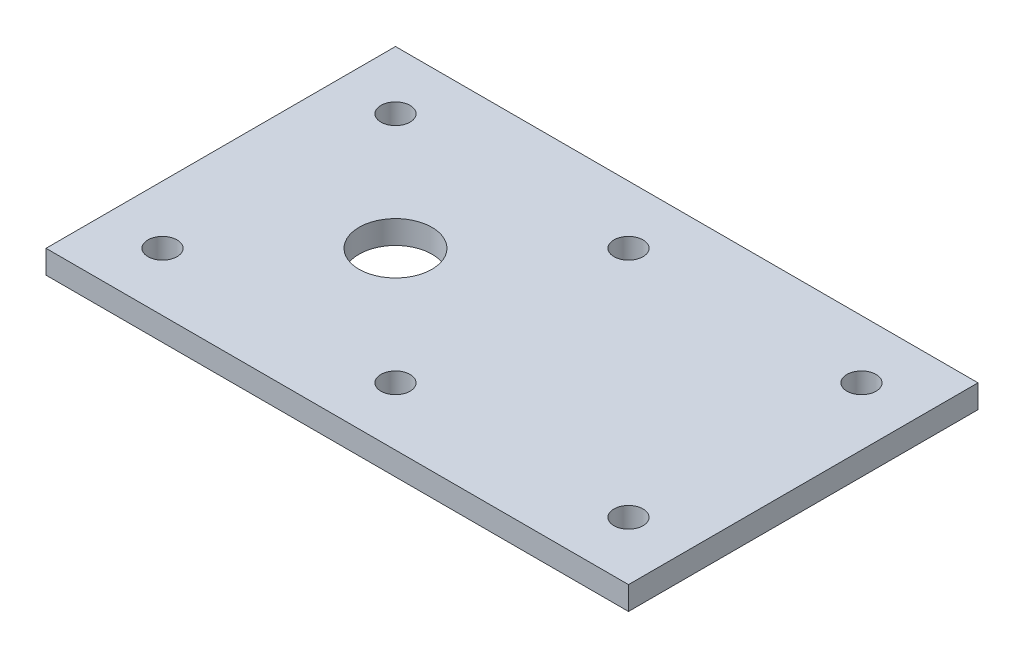
SolidWorks part; units mm, degrees
ref_plane "Front Plane" through (0, 0, 0) normal (0, 0, 1) x (1, 0, 0)
ref_plane "Top Plane" through (0, 0, 0) normal (0, 1, 0) x (1, 0, 0)
ref_plane "Right Plane" through (0, 0, 0) normal (1, 0, 0) x (0, 0, -1)
sketch "Sketch1" plane through (0, 0, 0) normal (0, 1, 0) x (1, 0, 0)
  line L0 (-60, 0) -> (140, 0) construction
  line L1 (-60, 60) -> (140, 60)
  line L2 (-60, 60) -> (-60, -60)
  line L3 (-60, -60) -> (140, -60)
  line L4 (140, 60) -> (140, -60)
  dimension "D1" = 200
  dimension "D2" = 120
  dimension "D3" = 60
extrude "Boss-Extrude5" add sketch "Sketch1" along normal blind 8
sketch "Sketch12" plane through (0, 8, 0) normal (0, 1, 0) x (1, 0, 0)
  line L1 (-60, 60) -> (-60, -60) construction
  line L2 (140, 60) -> (-60, 60) construction
  circle A0 centre (-40, 40) radius 5
  dimension "D1" = 10
  dimension "D2" = 20
  dimension "D3" = 20
extrude "Cut-Extrude1" cut sketch "Sketch12" against normal through all
pattern_linear "LPattern1" count 2 spacing 80 along (0, 0, 1) count 3 spacing 80 along (1, 0, 0) of "Cut-Extrude1"
sketch "Sketch13" plane through (0, 8, 0) normal (0, 1, 0) x (1, 0, 0)
  circle A0 centre (0, 0) radius 12.5
  dimension "D1" = 25
extrude "Cut-Extrude2" cut sketch "Sketch13" against normal blind 8
